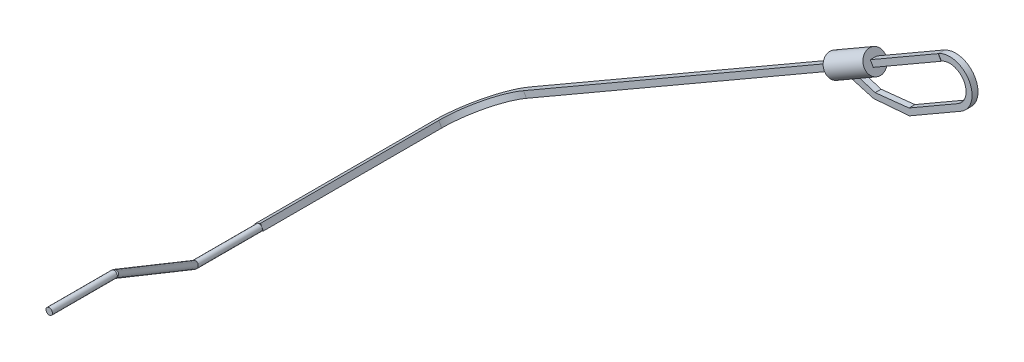
SolidWorks part; units mm, degrees
ref_plane "Front Plane" through (0, 0, 0) normal (0, 0, 1) x (1, 0, 0)
ref_plane "Top Plane" through (0, 0, 0) normal (0, 1, 0) x (1, 0, 0)
ref_plane "Right Plane" through (0, 0, 0) normal (1, 0, 0) x (0, 0, -1)
sketch3d "Plane points - Tendon captive tail"
  point P0 (-14.854, 2.0876, 25.9599)
  point P1 (2.9708, -0.4175, 25.9599)
  point P2 (-12.3489, 19.9124, 25.9599)
ref_plane "Drilling plane - Tendon captive tail" through (0, 0, 25.9599) normal (0, 0, 1) x (1, 0, 0)
sketch "S01 - Tendon captive tail" plane through (0, 0, 25.9599) normal (0, 0, 1) x (1, 0, 0)
  circle A0 centre (-14.854, 2.0876) radius 0.6
  dimension "D1" = 1.2
  dimension "D2" = 14.854
  dimension "D3" = 2.0876
extrude "01 - Tendon captive tail" add sketch "S01 - Tendon captive tail" along normal blind 12
sketch3d "Plane points - Crossed tendon"
  point P0 (-25.9808, -15, 0)
  point P1 (-41.0648, -5.1779, 0)
  point P2 (-33.7049, -26.8622, 11.1187)
ref_plane "Drilling plane - Crossed tendon" through (-5.5689, -8.5523, -12.9929) normal (0.3371, 0.5176, 0.7864) x (0.9415, -0.1853, -0.2815)
sketch "S02 - Crossed tendon" plane through (-5.5689, -8.5523, -12.9929) normal (0.3371, 0.5176, 0.7864) x (0.9415, -0.1853, -0.2815)
  circle A0 centre (-21.6806, -12.5293) radius 0.6
  dimension "D1" = 1.2
  dimension "D2" = 21.6806
  dimension "D3" = 12.5293
extrude "02 - Crossed tendon" add sketch "S02 - Crossed tendon" along normal blind 33.0107
sketch3d "Plane points - Tendon through rear grommet"
  point P0 (-25.9808, -15, -12)
  point P1 (-7.9808, -15, -12)
  point P2 (-25.9808, 3, -12)
ref_plane "Drilling plane - Tendon through rear grommet" through (0, 0, -12) normal (0, 0, 1) x (1, 0, 0)
sketch "S03 - Tendon through rear grommet" plane through (0, 0, -12) normal (0, 0, 1) x (1, 0, 0)
  circle A0 centre (-25.9808, -15) radius 0.6
  dimension "D1" = 1.2
  dimension "D2" = 25.9808
  dimension "D3" = 15
extrude "03 - Tendon through rear grommet" add sketch "S03 - Tendon through rear grommet" along normal blind 12
sketch3d "Plane points - Tendon return"
  point P0 (-18.1865, -10.5, -45)
  point P1 (-2.5981, -1.5, -45)
  point P2 (-18.1865, -10.5, -27)
ref_plane "Drilling plane - Tendon return" through (0, 0, 0) normal (0.5, -0.866, 0) x (-0.866, -0.5, 0)
sketch "S04 - Tendon return" plane through (0, 0, 0) normal (0.5, -0.866, 0) x (-0.866, -0.5, 0)
  line L0 (30.6, 12) -> (30.6, 45)
  line L1 (21, 54.6) -> (-67.5985, 54.6)
  line L2 (-67.5985, 54.6) -> (-67.5985, 53.4)
  line L3 (-67.5985, 53.4) -> (21, 53.4)
  line L4 (29.4, 45) -> (29.4, 12)
  line L5 (29.4, 12) -> (30.6, 12)
  arc A0 (30.6, 45) -> (21, 54.6) centre (21, 45) ccw
  arc A1 (21, 53.4) -> (29.4, 45) centre (21, 45) cw
  dimension "D1" = 9.6
  dimension "D2" = 8.4
  dimension "D3" = 29.4
  dimension "D4" = 67.5985
  dimension "D5" = 12
  dimension "D6" = 53.4
extrude "04 - Tendon return" add sketch "S04 - Tendon return" along normal blind 1.1 from offset 0.55
sketch3d "Plane points - Removable backed eye around polished clevis sleeve"
  point P0 (60.342, 30.6816, -54)
  point P1 (75.9305, 39.6816, -54)
  point P2 (51.342, 46.27, -54)
ref_plane "Drilling plane - Removable backed eye around polished clevis sleeve" through (0, 0, -54) normal (0, 0, 1) x (1, 0, 0)
sketch "S05 - Removable backed eye around polished clevis sleeve" plane through (0, 0, -54) normal (0, 0, 1) x (1, 0, 0)
  line L0 (58.0938, 34.1756) -> (58.267, 34.2756)
  line L1 (62.417, 27.0876) -> (52.8907, 21.5876)
  line L2 (52.8907, 21.5876) -> (46.2696, 21.0557)
  line L3 (46.2696, 21.0557) -> (40.7555, 22.6064)
  line L4 (40.7555, 22.6064) -> (41.2215, 23.7993)
  line L5 (41.2215, 23.7993) -> (46.5624, 22.1485)
  line L6 (46.5624, 22.1485) -> (52.8171, 22.8152)
  line L7 (52.8171, 22.8152) -> (61.867, 28.0402)
  line L8 (58.817, 33.3229) -> (58.6438, 33.2229)
  line L9 (58.6438, 33.2229) -> (58.0938, 34.1756)
  arc A0 (58.267, 34.2756) -> (62.417, 27.0876) centre (60.342, 30.6816) cw
  arc A1 (61.867, 28.0402) -> (58.817, 33.3229) centre (60.342, 30.6816) ccw
  dimension "D1" = 4.15
  dimension "D2" = 3.05
  dimension "D3" = 40.7555
  dimension "D4" = 41.2215
  dimension "D5" = 46.2696
  dimension "D6" = 46.5624
  dimension "D7" = 52.8171
  dimension "D8" = 52.8907
  dimension "D9" = 58.0938
  dimension "D10" = 58.267
  dimension "D11" = 58.6438
  dimension "D12" = 58.817
  dimension "D13" = 60.342
  dimension "D14" = 61.867
  dimension "D15" = 62.417
  dimension "D16" = 21.0557
  dimension "D17" = 21.5876
  dimension "D18" = 22.1485
  dimension "D19" = 22.6064
  dimension "D20" = 22.8152
  dimension "D21" = 23.7993
  dimension "D22" = 27.0876
  dimension "D25" = 33.2229
  dimension "D27" = 34.1756
extrude "05 - Removable backed eye around polished clevis sleeve" add sketch "S05 - Removable backed eye around polished clevis sleeve" along normal blind 1.1 from offset 0.55
sketch3d "Plane points - Dressed eye knot envelope"
  point P0 (38.6234, 22.2993, -54)
  point P1 (29.6234, 37.8877, -54)
  point P2 (38.6234, 22.2993, -36)
ref_plane "Drilling plane - Dressed eye knot envelope" through (38.6234, 22.2993, 0) normal (0.866, 0.5, 0) x (0, 0, -1)
sketch "S06 - Dressed eye knot envelope" plane through (38.6234, 22.2993, 0) normal (0.866, 0.5, 0) x (0, 0, -1)
  circle A0 centre (54, 0) radius 2
  dimension "D1" = 4
  dimension "D2" = 54
extrude "06 - Dressed eye knot envelope" add sketch "S06 - Dressed eye knot envelope" along normal blind 8.5
